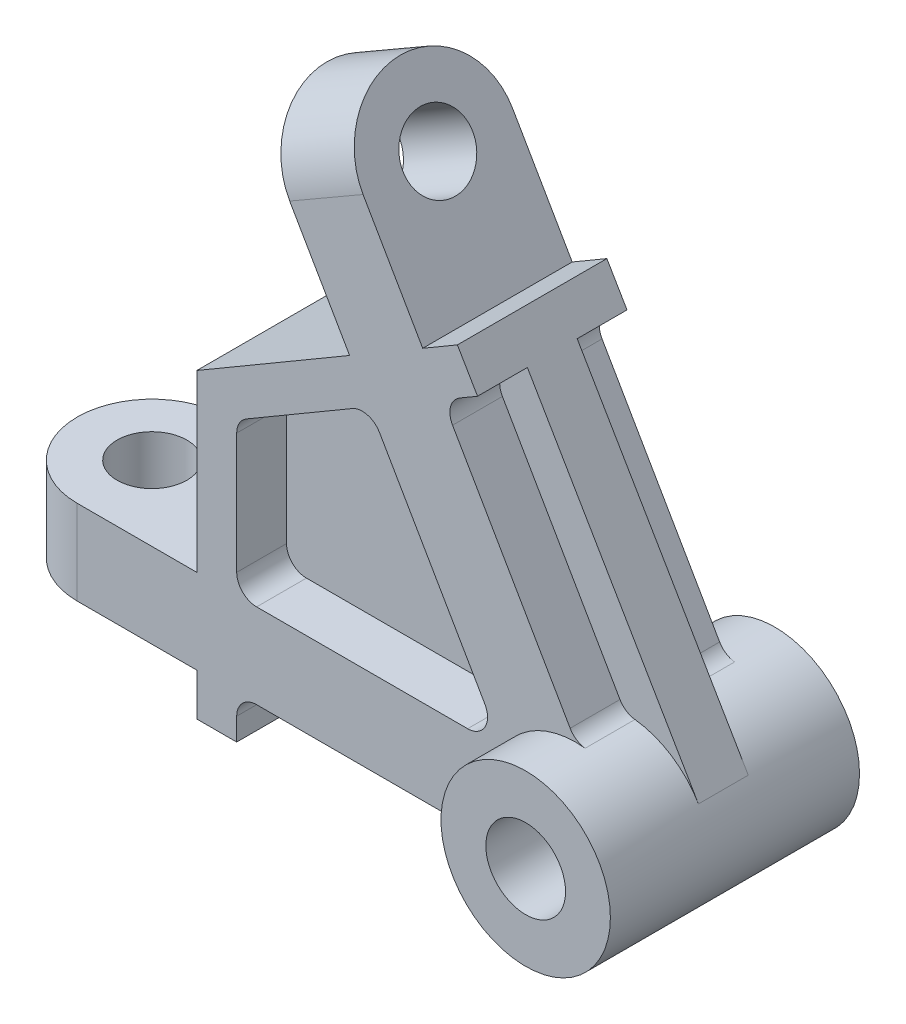
SolidWorks part; units mm, degrees
ref_plane "Front Plane" through (0, 0, 0) normal (0, 0, 1) x (1, 0, 0)
ref_plane "Top Plane" through (0, 0, 0) normal (0, 1, 0) x (1, 0, 0)
ref_plane "Right Plane" through (0, 0, 0) normal (1, 0, 0) x (0, 0, -1)
sketch "Sketch1" plane through (0, 0, 0) normal (0, 0, 1) x (1, 0, 0)
  circle A0 centre (0, 0) radius 20
  circle A1 centre (0, 0) radius 42.5
  dimension "D1" = 40
  dimension "D2" = 85
extrude "Boss-Extrude1" add sketch "Sketch1" along normal mid plane 125
sketch "Sketch2" plane through (0, 0, 0) normal (0, 1, 0) x (1, 0, 0)
  line L0 (-20, 62.5) -> (-20, -62.5)
  line L1 (-20, 37.5) -> (-20, -37.5)
  line L2 (-20, -37.5) -> (-250, -37.5)
  line L3 (-20, 37.5) -> (-250, 37.5)
  arc A0 (-250, -37.5) -> (-250, 37.5) centre (-250, 0) cw
  circle A1 centre (-250, 0) radius 17.5
  dimension "D1" = 35
  dimension "D2" = 37.5
  dimension "D3" = 250
extrude "Boss-Extrude2" add sketch "Sketch2" along normal mid plane 42.5 contours A0 L2 L0 L3 A1
pattern_circular "CirPattern1" count 2 over 360 about axis through (0, 0, 62.5) along (0, 0, 1) of "Boss-Extrude2"
sketch "Sketch3" plane through (0, 0, 0) normal (0, 0, 1) x (1, 0, 0)
  line L0 (0, -42.5) -> (-170, -42.5)
  line L1 (-170, -42.5) -> (-170, 97.5)
  line L2 (-170, 97.5) -> (-49.1603, 168.1949)
  line L3 (-49.1603, 168.1949) -> (36.6835, 21.4609)
  circle A0 centre (0, 0) radius 20 construction
  circle A1 centre (0, 0) radius 42.5 construction
  circle A2 centre (0, 0) radius 20
  arc A3 (0, -42.5) -> (36.6835, 21.4609) centre (0, 0) ccw
  point P10 (0, 0)
  dimension "D1" = 170
  dimension "D2" = 140
extrude "Boss-Extrude3" add sketch "Sketch3" along normal mid plane 25
sketch "Sketch4" plane through (0, 0, 0) normal (0, 0, 1) x (1, 0, 0)
  line L0 (-103.3434, 136.4961) -> (-170, 97.5) construction
  line L1 (-170, 97.5) -> (-170, 21.25) construction
  line L2 (-49.1603, 168.1949) -> (-170, 97.5)
  line L3 (-170, 97.5) -> (-170, -42.5)
  line L4 (-170, -42.5) -> (0, -42.5) construction
  line L5 (36.6835, 21.4609) -> (-49.1603, 168.1949) construction
  line L6 (-59.2596, 185.4577) -> (-190, 108.9706)
  line L7 (-190, 108.9706) -> (-190, -42.5)
  line L8 (-59.2596, 185.4577) -> (-49.1603, 168.1949)
  line L9 (-170, -42.5) -> (-190, -42.5)
  dimension "D1" = 20
extrude "Boss-Extrude4" add sketch "Sketch4" along normal mid plane 75
fillet "Fillet1" radius 10 16 edges at (0, 42.5, -25) (0, 42.5, 25) (-66.6594, 157.9574, 25) (-66.6594, 157.9574, -25) (-36.8061, -21.25, -25) (-170, -21.25, -25) (-36.8061, 21.25, 25) (-36.8061, 21.25, -25) (-170, 21.25, -25) (-170, 97.5, -25) (-103.3434, 136.4961, 25) (-103.3434, 136.4961, -25) (-36.8061, -21.25, 25) (-170, -21.25, 25) (-170, 97.5, 25) (-170, 21.25, 25)
